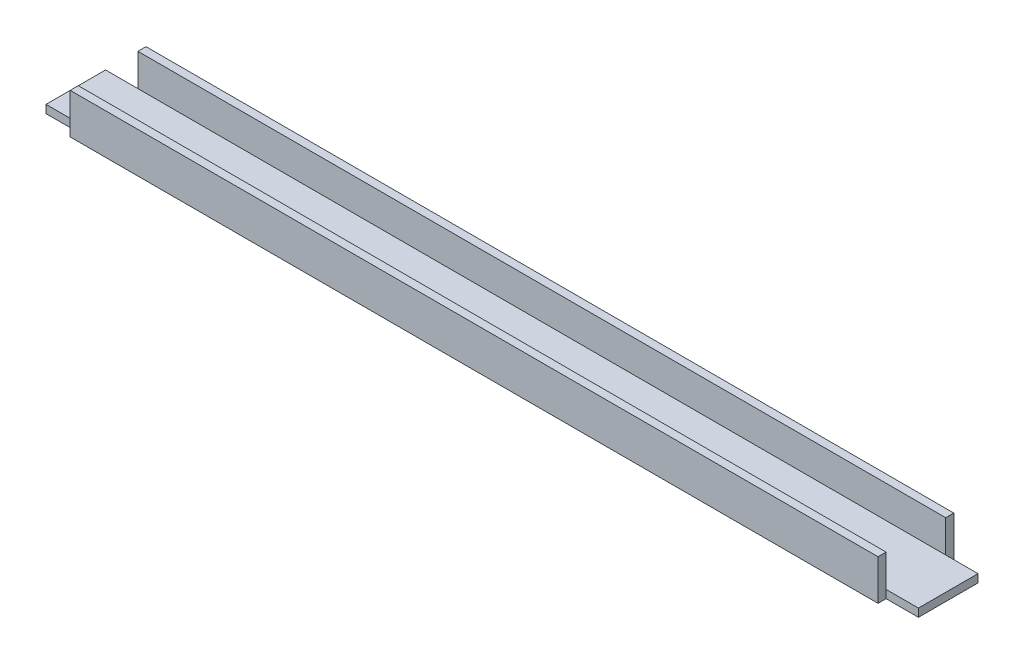
SolidWorks part; units mm, degrees
ref_plane "Front Plane" through (0, 0, 0) normal (0, 0, 1) x (1, 0, 0)
ref_plane "Top Plane" through (0, 0, 0) normal (0, 1, 0) x (1, 0, 0)
ref_plane "Right Plane" through (0, 0, 0) normal (1, 0, 0) x (0, 0, -1)
sketch "Sketch1" plane through (0, 0, 0) normal (0, 0, 1) x (1, 0, 0)
  line L0 (-400, 0) -> (400, 0)
  point P4 (0, 0)
  dimension "D1" = 800
other "C channel 80 X 8(1)"
ref_plane "Plane1" through (-400, 0, 0) normal (1, 0, 0) x (0, 1, 0)
sketch "Sketch11" plane through (-400, 0, 0) normal (1, 0, 0) x (0, 1, 0)
  line L0 (0, -37.5) -> (0, 37.5)
  line L1 (0, 37.5) -> (40, 37.5)
  line L2 (40, 37.5) -> (40, 29.5)
  line L3 (40, 29.5) -> (8, 29.5)
  line L4 (8, 29.5) -> (8, -29.5)
  line L5 (8, -29.5) -> (40, -29.5)
  line L6 (40, -29.5) -> (40, -37.5)
  line L7 (40, -37.5) -> (0, -37.5)
  point P3 (0, 0)
  dimension "D4" = 8
  dimension "D2" = 75
  dimension "D1" = 40
  dimension "D3" = 8
sketch "Sketch12" plane through (0, 0, 0) normal (0, -1, 0) x (1, 0, 0)
  line L0 (-400, 37.5) -> (-400, -37.5) construction
  line L1 (-400, -29.5) -> (-432, -29.5)
  line L2 (-400, -29.5) -> (-400, 29.5)
  line L3 (-400, 29.5) -> (-432, 29.5)
  line L4 (-432, -29.5) -> (-432, 29.5)
  line L5 (0, 0) -> (0, 153.5336) construction
  line L6 (432, -29.5) -> (432, 29.5)
  line L7 (400, 29.5) -> (432, 29.5)
  line L8 (400, -29.5) -> (400, 29.5)
  line L9 (400, -29.5) -> (432, -29.5)
  point P6 (-400, 0)
  dimension "D1" = 59
  dimension "D2" = 32
extrude "Boss-Extrude1" add sketch "Sketch12" against normal blind 8
